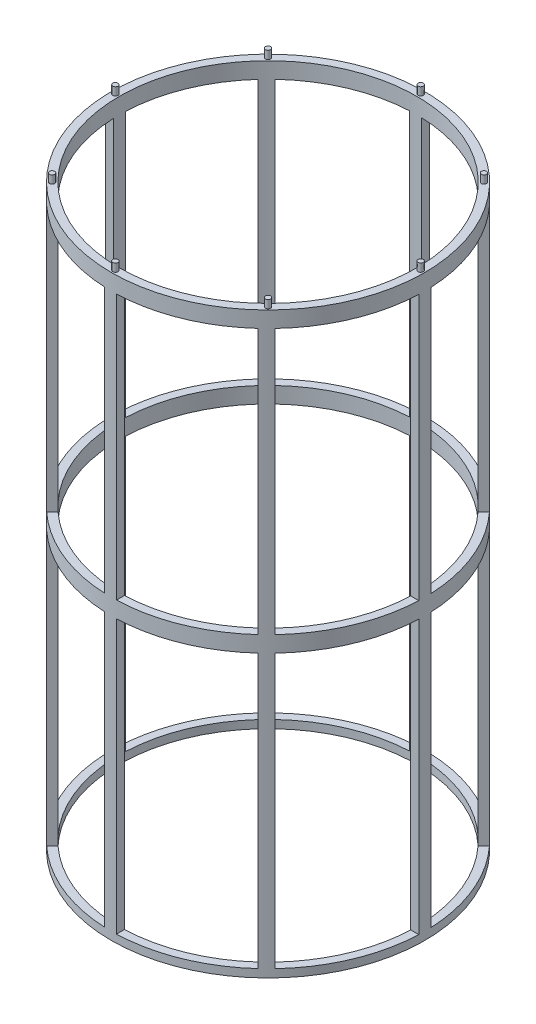
SolidWorks part; units mm, degrees
ref_plane "Front Plane" through (0, 0, 0) normal (0, 0, 1) x (1, 0, 0)
ref_plane "Top Plane" through (0, 0, 0) normal (0, 1, 0) x (1, 0, 0)
ref_plane "Right Plane" through (0, 0, 0) normal (1, 0, 0) x (0, 0, -1)
sketch "Sketch1" plane through (0, 0, 0) normal (0, 1, 0) x (1, 0, 0)
  circle A0 centre (0, 0) radius 49.53
  circle A1 centre (0, 0) radius 46.99
  dimension "D1" = 99.06
  dimension "D2" = 93.98
extrude "Boss-Extrude1" add sketch "Sketch1" along normal mid plane 365.76
sketch "Sketch2" plane through (0, 0, 0) normal (0, 1, 0) x (1, 0, 0)
  line L0 (0, -49.53) -> (0, 49.53) construction
  line L1 (49.53, 0) -> (-49.53, 0) construction
  line L2 (36.1361, -33.8733) -> (-33.8733, 36.1361)
  line L3 (49.4953, -1.8543) -> (-49.4953, -1.8543)
  line L5 (49.4914, 1.9557) -> (-49.4914, 1.9557)
  line L7 (49.5079, -1.4801) -> (-49.5079, 1.4801) construction
  line L8 (49.5079, 1.4801) -> (-49.5079, -1.4801) construction
  line L10 (-2.2251, -49.48) -> (-2.2251, 49.48)
  line L12 (1.5849, -49.5046) -> (1.5849, 49.5046)
  line L13 (-2.0946, -49.4857) -> (2.0946, 49.4857) construction
  line L14 (-2.0946, 49.4857) -> (2.0946, -49.4857) construction
  line L17 (33.4254, -36.5508) -> (-36.5508, 33.4254)
  line L18 (36.2203, -33.7833) -> (-36.2203, 33.7833) construction
  line L19 (-33.7833, 36.2203) -> (33.7833, -36.2203) construction
  line L20 (-36.2459, -33.7558) -> (33.7558, 36.2459)
  line L23 (-33.544, -36.4421) -> (36.4421, 33.544)
  line L24 (-35.9086, -34.1144) -> (35.9086, 34.1144) construction
  line L25 (34.1144, 35.9086) -> (-34.1144, -35.9086) construction
  line L26 (42.4888, -20.0689) -> (-44.235, 15.8533)
  line L29 (43.9751, -16.5606) -> (-42.8052, 19.385)
  line L30 (42.7791, -19.4425) -> (-42.7791, 19.4425) construction
  line L31 (-43.9973, 16.5014) -> (43.9973, -16.5014) construction
  line L32 (19.1177, -42.9252) -> (-16.8344, 43.871)
  line L35 (15.577, -44.333) -> (-20.3336, 42.3628)
  line L36 (19.8255, -42.6029) -> (-19.8255, 42.6029) construction
  line L37 (-16.1061, 44.1436) -> (16.1061, -44.1436) construction
  line L38 (-16.6796, -43.9301) -> (19.2689, 42.8575)
  line L41 (-20.184, -42.4343) -> (15.7333, 44.2778)
  line L42 (-16.127, -44.1359) -> (16.127, 44.1359) construction
  line L43 (19.8053, 42.6123) -> (-19.8053, -42.6123) construction
  line L44 (-44.26, -15.7832) -> (42.457, 20.1362)
  line L47 (-42.8358, -19.3171) -> (43.9488, 16.6302)
  line L48 (-44.0599, -16.3335) -> (44.0599, 16.3335) construction
  line L49 (42.7046, 19.6055) -> (-42.7046, -19.6055) construction
  circle A0 centre (0, 0) radius 49.53
  circle A1 centre (0, 0) radius 46.99
  point P7 (0, 0)
  point P10 (0, 0)
  dimension "D1" = 45
  dimension "D2" = 45
  dimension "D3" = 22.5
  dimension "D4" = 22.5
  dimension "D5" = 22.5
  dimension "D6" = 22.5
  dimension "D7" = 3.81
  dimension "D8" = 3.81
  dimension "D9" = 3.81
  dimension "D10" = 3.81
  dimension "D11" = 3.81
  dimension "D12" = 3.81
  dimension "D13" = 3.81
  dimension "D14" = 3.81
extrude "Cut-Extrude1" cut sketch "Sketch2" against normal mid plane 355.6 contours A1 L10 A0 L2 | A1 L17 A0 L5 | A1 L3 A0 L20 | A1 L23 A0 L10 | A1 L12 A0 L17 | A1 L2 A0 L3 | A1 L5 A0 L23 | A1 L20 A0 L12 L35
ref_plane "Plane1" through (0, 91.44, 0) normal (0, 1, 0) x (1, 0, 0)
sketch "Sketch3" plane through (0, 91.44, 0) normal (0, 1, 0) x (1, 0, 0)
  circle A0 centre (0, 0) radius 46.99
  circle A1 centre (0, 0) radius 49.53
extrude "Boss-Extrude2" add sketch "Sketch3" along normal mid plane 5.08
mirror "Mirror1" about plane through (0, 0, 0) normal (0, 1, 0) of "Boss-Extrude2"
sketch "Sketch4" plane through (0, 0, 0) normal (0, 1, 0) x (1, 0, 0)
  circle A0 centre (0, 0) radius 46.99
  circle A1 centre (0, 0) radius 49.53
extrude "Boss-Extrude3" add sketch "Sketch4" along normal mid plane 5.08
sketch "Sketch5" plane through (0, -182.88, 0) normal (0, -1, 0) x (1, 0, 0)
  circle A0 centre (0, 0) radius 49.53
extrude "Boss-Extrude4" add sketch "Sketch5" against normal blind 5.08
sketch "Sketch6" plane through (0, -177.8, 0) normal (0, 1, 0) x (1, 0, 0)
  line L0 (0, -49.53) -> (0, 49.53) construction
  line L1 (49.53, 0) -> (-49.53, 0) construction
  line L3 (25.2095, -2.3495) -> (-25.2095, -2.3495)
  line L4 (25.2095, -2.3495) -> (25.2095, 2.3495)
  line L5 (25.2095, 2.3495) -> (-25.2095, 2.3495)
  line L6 (-25.2095, -2.3495) -> (-25.2095, 2.3495)
  line L7 (25.2095, -2.3495) -> (-25.2095, 2.3495) construction
  line L8 (25.2095, 2.3495) -> (-25.2095, -2.3495) construction
  circle A0 centre (0, 0) radius 49.53 construction
  point P0 (0, 0)
  point P7 (0, 0)
  point P11 (0, 0)
  dimension "D1" = 50.419
  dimension "D2" = 4.699
extrude "Boss-Extrude5" add sketch "Sketch6" along normal blind 2.54
sketch "Sketch7" plane through (0, 182.88, 0) normal (0, 1, 0) x (1, 0, 0)
  line L0 (0, 49.53) -> (0, -49.53) construction
  line L1 (49.53, 0) -> (46.99, 0) construction
  line L2 (0, 0) -> (-49.53, 0) construction
  circle A1 centre (0, 0) radius 49.53 construction
  circle A2 centre (0, 0) radius 46.99 construction
  circle A3 centre (48.26, 0) radius 0.8255
  point P8 (0, 0)
  point P11 (0, 0)
  dimension "D1" = 1.651
  dimension "D2" = 1.27
extrude "Boss-Extrude6" add sketch "Sketch7" along normal blind 2.54
pattern_circular "CirPattern2" count 8 over 360 about axis through (0, 0, 0) along (0, 1, 0) of "Boss-Extrude6"
sketch "Sketch8" plane through (0, 0, 0) normal (1, 0, 0) x (0, 0, -1)
  line L0 (36.2459, -2.54) -> (49.5046, -2.54) construction
  line L1 (68.6804, 0) -> (-63.7181, 0)
  line L2 (68.6804, 0) -> (68.6804, -191.0491)
  line L3 (68.6804, -191.0491) -> (-63.7181, -191.0491)
  line L4 (-63.7181, 0) -> (-63.7181, -191.0491)
  dimension "D1" = 2.54
extrude "Cut-Extrude2" cut sketch "Sketch8" against normal through all both and the other way through all
